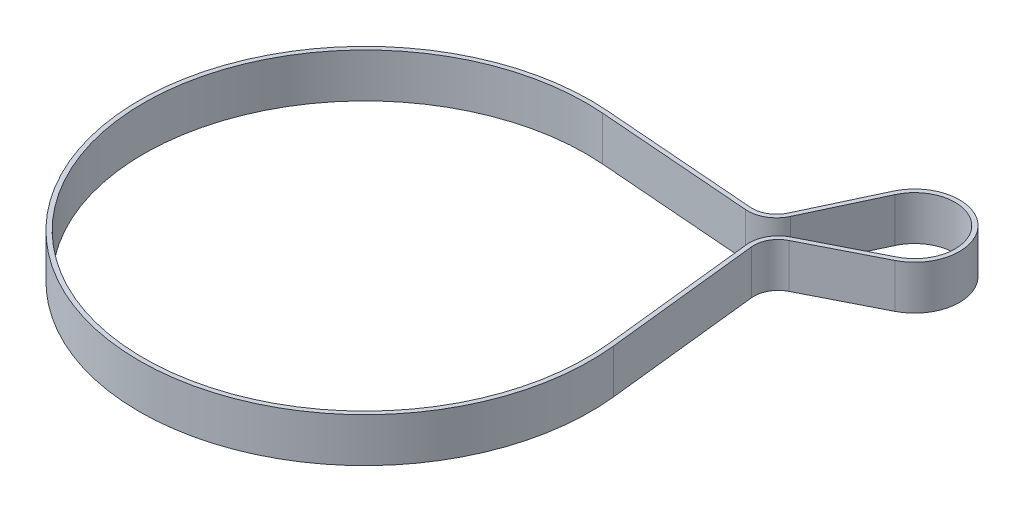
SolidWorks part; units mm, degrees
ref_plane "Front Plane" through (0, 0, 0) normal (0, 0, 1) x (1, 0, 0)
ref_plane "Top Plane" through (0, 0, 0) normal (0, 1, 0) x (1, 0, 0)
ref_plane "Right Plane" through (0, 0, 0) normal (1, 0, 0) x (0, 0, -1)
sketch "Sketch1" plane through (0, 0, 0) normal (0, 1, 0) x (1, 0, 0)
  line L0 (-9.8802, 43.8429) -> (-2.2924, 60.0255)
  line L1 (-10.7856, 44.2675) -> (-3.1978, 60.4501)
  line L2 (-5.3299, 38.978) -> (10.6104, 47.0624)
  line L3 (-5.7823, 39.8698) -> (10.158, 47.9543)
  line L4 (-51.3457, 43.8565) -> (-16.1923, 41.119)
  line L5 (-51.4234, 42.8595) -> (-16.27, 40.122)
  line L6 (-9.3038, 33.368) -> (-5.4809, -1.6839)
  line L7 (-4.4868, -1.5755) -> (-8.3097, 33.4764)
  circle A0 centre (6.0102, 56.1326) radius 9.17
  circle A1 centre (-55.3153, -7.1192) radius 50.13
  circle A2 centre (-15.7653, 46.6024) radius 5.5
  circle A3 centre (-2.8422, 34.0728) radius 5.5
  circle A4 centre (6.0102, 56.1326) radius 10.17
  circle A5 centre (-15.7653, 46.6024) radius 6.5
  circle A6 centre (-2.8422, 34.0728) radius 6.5
  circle A7 centre (-55.3153, -7.1192) radius 51.13
extrude "Boss-Extrude1" add sketch "Sketch1" along normal blind 10 contours A7 L6 A1 L5 | A7 L5 A5 L4 | A5 L1 A2 L4 | A7 L7 A6 L6 | L2 A6 L7 A3 | A6 L2 A4 L3 | A5 L0 A4 L1 | L3 A4 L0 A0
